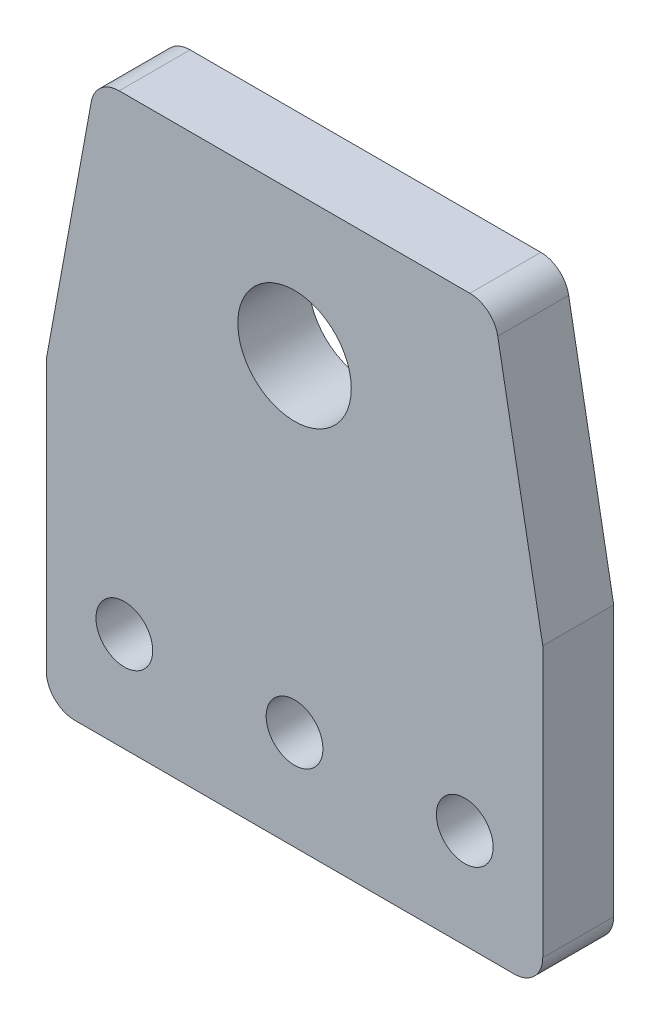
SolidWorks part; units mm, degrees
ref_plane "前视基准面" through (0, 0, 0) normal (0, 0, 1) x (1, 0, 0)
ref_plane "上视基准面" through (0, 0, 0) normal (0, 1, 0) x (1, 0, 0)
ref_plane "右视基准面" through (0, 0, 0) normal (1, 0, 0) x (0, 0, -1)
sketch "草图1" plane through (0, 0, 0) normal (0, 0, 1) x (1, 0, 0)
  line L0 (2, 0) -> (33, 0)
  line L7 (35, 2) -> (35, 21.0503)
  line L8 (35, 21.0503) -> (31.8281, 38.3605)
  line L9 (29.8609, 40) -> (5.1391, 40)
  line L10 (3.1719, 38.3605) -> (0, 21.0503)
  line L11 (0, 21.0503) -> (0, 2)
  line L12 (17.5, 0.6527) -> (17.5, 34.1383) construction
  arc A0 (33, 0) -> (35, 2) centre (33, 2) ccw
  arc A1 (2, 0) -> (0, 2) centre (2, 2) cw
  arc A2 (5.1391, 40) -> (3.1719, 38.3605) centre (5.1391, 38) ccw
  arc A3 (31.8281, 38.3605) -> (29.8609, 40) centre (29.8609, 38) ccw
  circle A4 centre (17.5, 30) radius 4
  circle A5 centre (17.5, 7) radius 2
  circle A6 centre (29.5, 7) radius 2
  circle A7 centre (5.5, 7) radius 2
  point P13 (0, 0)
  point P16 (3.4723, 40)
  point P19 (31.5277, 40)
  dimension "D1" = 2
  dimension "D2" = 2
  dimension "D3" = 2
  dimension "D4" = 2
  dimension "D7" = 8
  dimension "D8" = 4
  dimension "D9" = 4
  dimension "D10" = 5.5
  dimension "D5" = 40
  dimension "D6" = 10
  dimension "D11" = 24
  dimension "D12" = 7
  dimension "D13" = 17.5
  dimension "D14" = 24.7217
  dimension "D15" = 169.616
extrude "凸台-拉伸1" add sketch "草图1" along normal blind 5
sketch "草图2" plane through (0, 0, 5) normal (0, 0, 1) x (1, 0, 0)
  line L0 (5.5, 7) -> (0, 7)
  line L1 (0, 21.0503) -> (0, 2) construction
